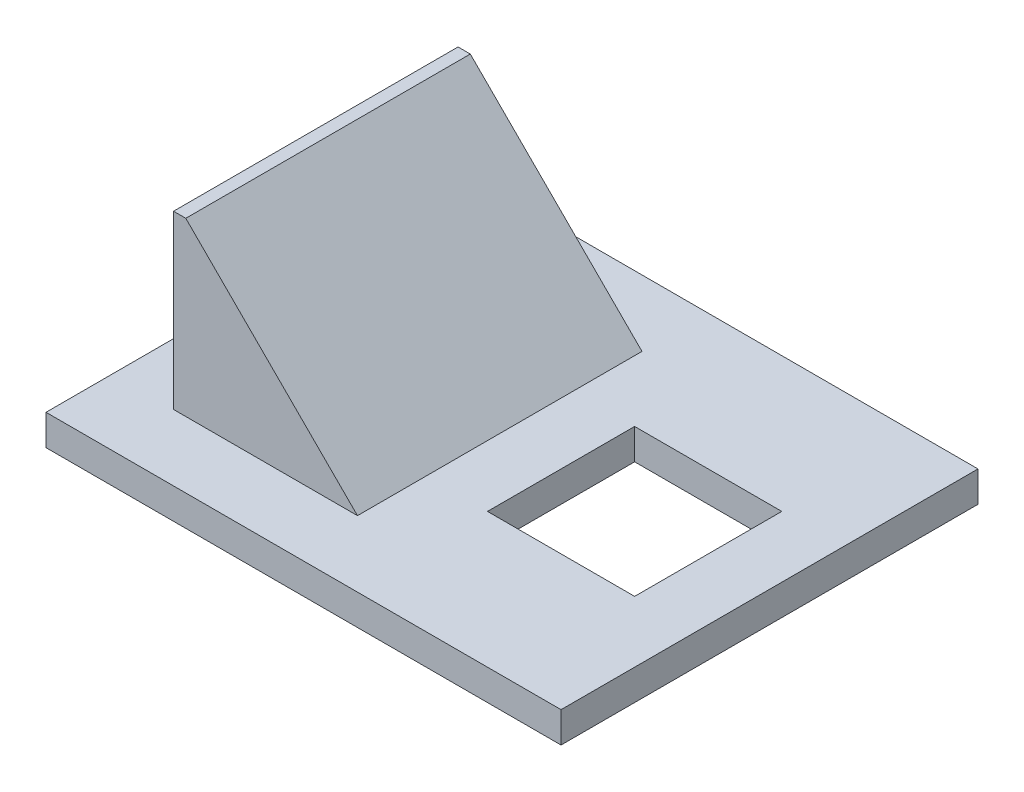
SolidWorks part; units mm, degrees
ref_plane "Спереди" through (0, 0, 0) normal (0, 0, 1) x (1, 0, 0)
ref_plane "Сверху" through (0, 0, 0) normal (0, 1, 0) x (1, 0, 0)
ref_plane "Справа" through (0, 0, 0) normal (1, 0, 0) x (0, 0, -1)
sketch "Эскиз1" plane through (0, 0, 0) normal (0, 1, 0) x (1, 0, 0)
  line L1 (-105, 85) -> (105, 85)
  line L2 (-105, 85) -> (-105, -85)
  line L3 (-105, -85) -> (105, -85)
  line L4 (105, 85) -> (105, -85)
  line L5 (0, -85) -> (0, 85) construction
  line L6 (-105, 0) -> (105, 0) construction
  point P180 (0, 0)
  dimension "D1" = 170
  dimension "D2" = 210
extrude "Бобышка-Вытянуть1" add sketch "Эскиз1" along normal blind 12.5
sketch "Эскиз2" plane through (0, 12.5, 0) normal (0, 1, 0) x (1, 0, 0)
  line L1 (105, 85) -> (-105, 85) construction
  line L2 (20, 30) -> (80, 30)
  line L3 (20, 30) -> (20, -30)
  line L4 (20, -30) -> (80, -30)
  line L5 (80, 30) -> (80, -30)
  line L6 (50, -30) -> (50, 30) construction
  line L7 (20, 0) -> (80, 0) construction
  line L9 (105, -85) -> (105, 85) construction
  point P126 (50, 0)
  dimension "D1" = 60
  dimension "D2" = 60
  dimension "D3" = 55
  dimension "D4" = 25
extrude "Вырез-Вытянуть1" cut sketch "Эскиз2" against normal blind 15
sketch "Эскиз3" plane through (0, 0, 0) normal (0, 1, 0) x (1, 0, 0)
  line L0 (105, 85) -> (-105, 85) construction
  line L1 (-80, 55) -> (-10, 55)
  line L2 (-80, 55) -> (-80, -55)
  line L3 (-80, -55) -> (-10, -55)
  line L4 (-10, 55) -> (-10, -55)
  line L5 (-45, -55) -> (-45, 55) construction
  line L6 (-80, 0) -> (-10, 0) construction
  line L7 (-105, 85) -> (-105, -85) construction
  point P96 (-45, 0)
  dimension "D1" = 110
  dimension "D2" = 70
  dimension "D3" = 30
  dimension "D4" = 25
extrude "Вырез-Вытянуть4" cut sketch "Эскиз3" along normal blind 20
sketch3d "Трехмерный эскиз1"
  line L0 (-10, 12.5, -55) -> (-10, 12.5, 55)
  line L1 (-10, 12.5, -55) -> (-80, 82.5, -55)
  line L2 (-10, 12.5, 55) -> (-80, 82.5, 55)
  line L3 (-80, 82.5, -55) -> (-80, 82.5, 55)
  line L4 (-10, 12.5, -55) -> (-10, 12.5, 55) construction
  line L5 (-80, 12.5, 55) -> (-80, 82.5, 55) construction
  line L7 (-80, 12.5, -55) -> (-80, 82.5, -55) construction
  line L9 (-80, 12.5, -55) -> (-10, 12.5, -55) construction
  dimension "D1" = 45
extrude "Бобышка-Вытянуть4" add sketch "Трехмерный эскиз1" along direction (-1, 0, 0) on the side of the normal blind 5
sketch3d "Трехмерный эскиз3"
  line L0 (-7.5, 12.5, -55) -> (-80, 12.5, -55)
  line L1 (-10, 12.5, -55) -> (-5, 12.5, -55) construction
  line L2 (-80, 12.5, -55) -> (-80, 82.5, -55)
  line L3 (-80, 82.5, -55) -> (-7.5, 12.5, -55)
extrude "Бобышка-Вытянуть6" add sketch "Трехмерный эскиз3" along direction (0, 0, -1) on the side against the normal blind 3
sketch3d "Трехмерный эскиз4"
  line L0 (-7.5, 12.5, 55) -> (-80, 82.5, 55)
  line L1 (-10, 12.5, 55) -> (-5, 12.5, 55) construction
  line L2 (-80, 82.5, 55) -> (-80, 12.5, 55)
  line L3 (-80, 12.5, 55) -> (-7.5, 12.5, 55)
extrude "Бобышка-Вытянуть7" add sketch "Трехмерный эскиз4" along direction (0, 0, 1) on the side of the normal blind 3
sketch "Эскиз7" plane through (0, 0, -55) normal (0, 0, -1) x (-1, 0, 0)
  line L0 (5, 12.5) -> (7.5, 12.5)
  line L1 (7.5, 12.5) -> (80, 82.5)
  line L2 (80, 82.5) -> (75, 82.5)
  line L3 (75, 82.5) -> (5, 12.5)
extrude "Бобышка-Вытянуть8" add sketch "Эскиз7" along normal blind 3
sketch3d "Трехмерный эскиз5"
  line L0 (-5, 12.5, 55) -> (-7.5, 12.5, 55)
  line L1 (-7.5, 12.5, 55) -> (-80, 82.5, 55)
  line L2 (-80, 82.5, 55) -> (-75, 82.5, 55)
  line L3 (-75, 82.5, 55) -> (-5, 12.5, 55)
extrude "Бобышка-Вытянуть9" add sketch "Трехмерный эскиз5" along direction (0, 0, 1) on the side against the normal blind 3
